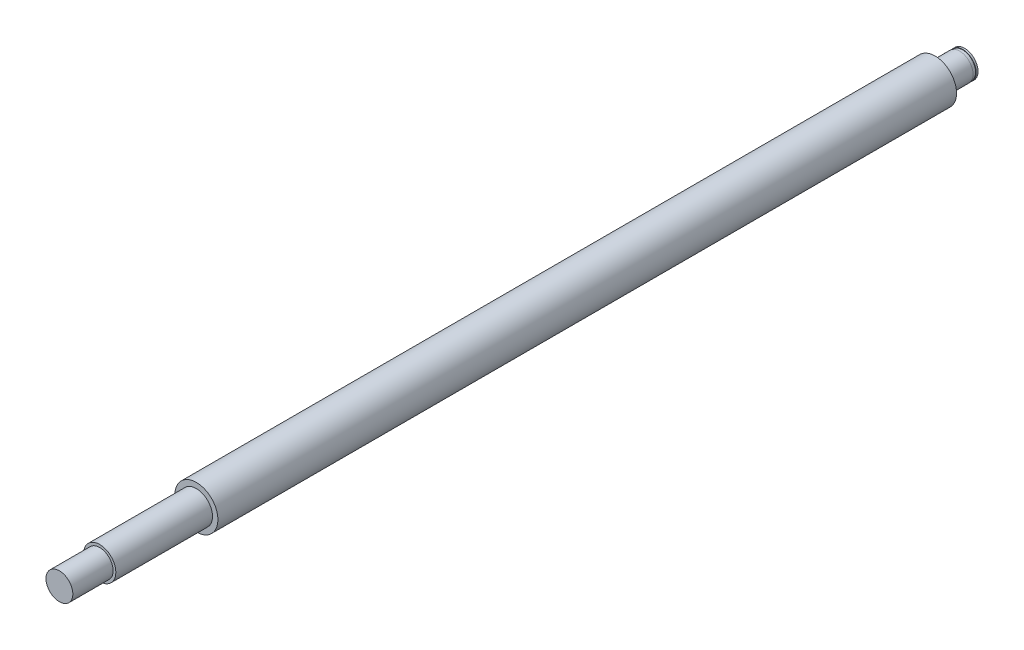
SolidWorks part; units mm, degrees
ref_plane "Plano frontal" through (0, 0, 0) normal (0, 0, 1) x (1, 0, 0)
ref_plane "Plano superior" through (0, 0, 0) normal (0, 1, 0) x (1, 0, 0)
ref_plane "Plano direito" through (0, 0, 0) normal (1, 0, 0) x (0, 0, -1)
sketch "Sketch1" plane through (0, 0, 0) normal (0, 0, 1) x (1, 0, 0)
  circle A0 centre (0, 0) radius 8
  dimension "D1" = 16
extrude "Boss-Extrude1" add sketch "Sketch1" against normal blind 275 contours A0
cosmetic thread "Cosmetic Thread3" parameters "D1"=275, "D2"=13.797
sketch "Sketch2" plane through (0, 0, 0) normal (0, 0, 1) x (1, 0, 0)
  circle A0 centre (0, 0) radius 6
  dimension "D1" = 12
extrude "Boss-Extrude2" add sketch "Sketch2" along normal blind 36
cosmetic thread "Cosmetic Thread1" parameters "D1"=14, "D2"=10.072
sketch "Sketch3" plane through (0, 0, 36) normal (0, 0, 1) x (1, 0, 0)
  circle A0 centre (0, 0) radius 5
  dimension "D1" = 10
extrude "Boss-Extrude3" add sketch "Sketch3" along normal blind 15
sketch "Sketch4" plane through (0, 0, -275) normal (0, 0, -1) x (-1, 0, 0)
  circle A0 centre (0, 0) radius 5
  dimension "D1" = 10
extrude "Boss-Extrude4" add sketch "Sketch4" along normal blind 9.15
sketch "Sketch5" plane through (0, 0, -284.15) normal (0, 0, -1) x (-1, 0, 0)
  circle A0 centre (0, 0) radius 4.8
  dimension "D1" = 9.6
extrude "Boss-Extrude5" add sketch "Sketch5" along normal blind 1.15 contours A0
sketch "Sketch7" plane through (0, 0, -285.3) normal (0, 0, -1) x (-1, 0, 0)
  circle A0 centre (0, 0) radius 5
  dimension "D1" = 10
extrude "Boss-Extrude6" add sketch "Sketch7" along normal blind 0.7
